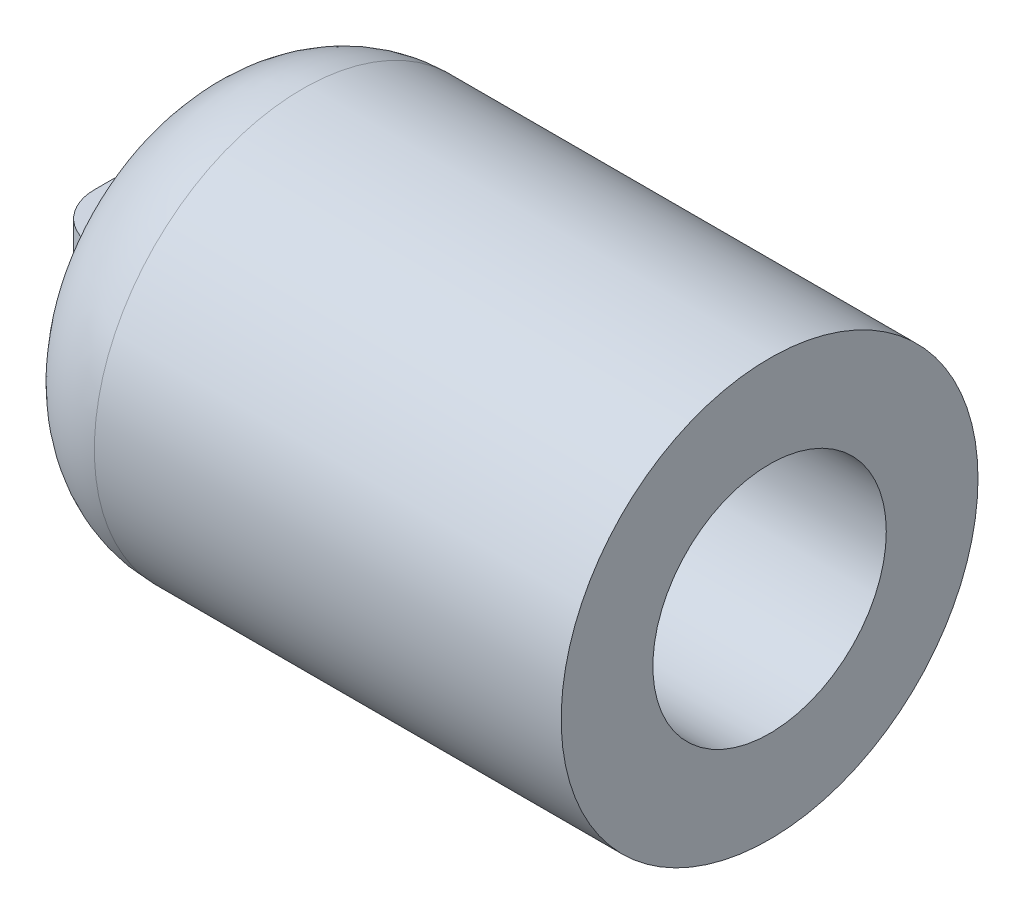
SolidWorks part; units mm, degrees
ref_plane "前视基准面" through (0, 0, 0) normal (0, 0, 1) x (1, 0, 0)
ref_plane "上视基准面" through (0, 0, 0) normal (0, 1, 0) x (1, 0, 0)
ref_plane "右视基准面" through (0, 0, 0) normal (1, 0, 0) x (0, 0, -1)
sketch "草图1" plane through (0, 0, 0) normal (1, 0, 0) x (0, 0, -1)
  circle A0 centre (0, 0) radius 12.5
  point P6 (0, 0)
  dimension "D1" = 25
extrude "凸台-拉伸1" add sketch "草图1" against normal blind 35
sketch "草图3" plane through (-35, 0, 0) normal (-1, 0, 0) x (0, 0, 1)
  line L0 (-0.8786, -12.4691) -> (0.8786, 12.4691)
  line L2 (3.5, 1.5) -> (-3.5, 1.5)
  line L3 (3.5, 1.5) -> (3.5, -1.5)
  line L4 (3.5, -1.5) -> (-3.5, -1.5)
  line L5 (-3.5, 1.5) -> (-3.5, -1.5)
  line L6 (3.5, 1.5) -> (-3.5, -1.5) construction
  line L7 (3.5, -1.5) -> (-3.5, 1.5) construction
  circle A0 centre (0, 0) radius 12.5 construction
  point P4 (0, 0)
  dimension "D1" = 3
  dimension "D2" = 7
extrude "凸台-拉伸2" add sketch "草图3" along normal blind 5 contours L3 L2 L5 L4
sketch "草图4" plane through (0, -1.5, 0) normal (0, -1, 0) x (1, 0, 0)
  line L0 (-40, -3.5) -> (-35, 3.5) construction
  line L1 (-35, -3.5) -> (-40, 3.5) construction
  circle A0 centre (-37.5, 0) radius 1.5
  dimension "D1" = 3
extrude "切除-拉伸1" cut sketch "草图4" against normal blind 5 contours A0
fillet "圆角1" radius 3 1 edges at (-40, 0, 3.5)
fillet "圆角2" radius 3 1 edges at (-40, 0, -3.5)
fillet "圆角3" radius 7 1 edges at (-35, 0, -12.5)
sketch3d "3D草图1"
  line L0 (-28, -4.6438, 11.6054) -> (0, -4.6438, 11.6054) construction
  circle A0 centre (-28, 0, 0) radius 12.5 construction
  circle A1 centre (0, 0, 0) radius 12.5 construction
  point P4 (-15.5, 0, 0)
  point P7 (12.5, 0, 0)
sketch "草图5" plane through (0, 0, 0) normal (1, 0, 0) x (0, 0, -1)
  circle A0 centre (0, 0) radius 7
  dimension "D1" = 14
extrude "切除-拉伸2" cut sketch "草图5" against normal blind 30
